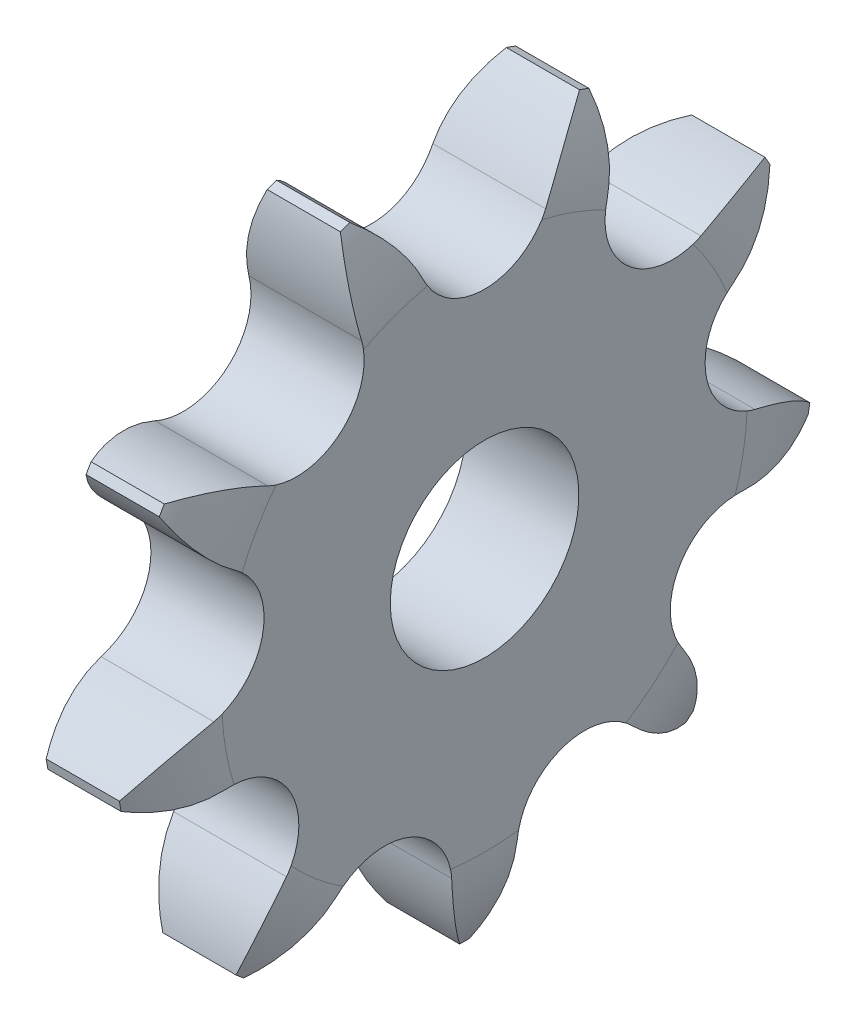
SolidWorks part; units mm, degrees
ref_plane "Plane1" through (0, 0, 0) normal (0, 0, 1) x (1, 0, 0)
ref_plane "Plane2" through (0, 0, 0) normal (0, 1, 0) x (1, 0, 0)
ref_plane "Plane3" through (0, 0, 0) normal (1, 0, 0) x (0, 0, -1)
sketch "Clipboard" plane through (0, 0, 0) normal (0, 1, 0) x (1, 0, 0)
  line L0 (0, 0) -> (12.5436, -1.9867)
  line L1 (-15, 0) -> (100, 0) construction
  line L2 (0, 0) -> (-0.8416, 0.9512)
  line L3 (0, 0) -> (-11.863, 4.5341)
  line L4 (0, 0) -> (3.0618, 0.4849)
  line L5 (0, 0) -> (-2.8109, -1.0484)
  line L6 (0, 0) -> (-5.9685, -4.027)
  line L7 (-0.8416, 0.9512) -> (8.4161, 2.5835)
  line L8 (-76.2, 38.1) -> (-75.2, 38.1)
  line L9 (-73.4259, 41.6592) -> (-72.8306, 41.7344)
  line L10 (-73.4741, 12.7512) -> (-59.5541, 12.7512)
  circle A0 centre (0, 0) radius 4.255
  circle A1 centre (0, 0) radius 10.9305
  circle A2 centre (0, 0) radius 25
  dimension "Dr" = 8.51
  dimension "MHD" = 21.861
  dimension "Hub_dia" = 50
  dimension "Num_teeth" = 9
  dimension "Pitch" = 12.7
  dimension "Width" = 3.1
  dimension "Side_relief" = 1.27
  dimension "Side_radius" = 12.7
  dimension "Overall_len" = 3
  dimension "Show_teeth" = 9
  dimension "Thickness" = 7.2
  dimension "OAL" = 9.4005
  dimension "T_dim" = 1
  dimension "Fillet_rad" = 0.6
  dimension "Face_width" = 7.2
  dimension "Num_strands" = 1
  dimension "Transv_pitch" = 13.92
  dimension "Plate_wid" = 11.8
sketch "BasProSke" plane through (0, 0, 0) normal (0, 1, 0) x (1, 0, 0)
  line L0 (-10, 0) -> (60, 0) construction
  line L1 (0, 0) -> (0, 16.7129)
  line L2 (0, 0) -> (7.2, 0)
  line L3 (7.2, 0) -> (7.2, 16.7129)
  line L4 (5.93, 22.2487) -> (1.27, 22.2487)
  arc A0 (0, 16.7129) -> (1.27, 22.2487) centre (12.7, 16.7129) cw
  arc A1 (7.2, 16.7129) -> (5.93, 22.2487) centre (-5.5, 16.7129) ccw
  dimension "Thickness" = 7.2
  dimension "D1" = 12.7
  dimension "G1" = 1.27
  dimension "G2" = 1.27
  dimension "Diameter" = 44.4973
revolve "Base-Revolve" add sketch "BasProSke" angle 360 about L0
sketch "TooCutSke" plane through (0, 0, 0) normal (1, 0, 0) x (0, 0, -1)
  line L0 (0, 18.6087) -> (3.8949, 16.7925) construction
  line L1 (0, 0) -> (0, 107) construction
  line L2 (0, 18.6087) -> (-10, 18.6087) construction
  line L3 (0, 18.6087) -> (-3.8949, 16.7925) construction
  arc A0 (3.8949, 16.7925) -> (7.8075, 21.3669) centre (14.0756, 12.0451) cw
  arc A1 (3.8949, 16.7925) -> (-3.8949, 16.7925) centre (0, 18.6087) cw
  arc A2 (-3.8949, 16.7925) -> (-7.8075, 21.3669) centre (-14.0756, 12.0451) ccw
  arc A3 (7.8075, 21.3669) -> (-7.8075, 21.3669) centre (0, 0) ccw
  dimension "R1" = 4.2976
  dimension "R2" = 11.2332
  dimension "Overcut" = 22.7487
  dimension "Seat_radius" = 18.6087
  dimension "X" = 130
extrude "ToothCut" cut sketch "TooCutSke" along normal through all
pattern_circular "TeethCuts" count 9 every 40 about axis through (-10, 0, 0) along (1, 0, 0) of "ToothCut"
sketch "HubNeaOneSke" plane through (0, 0, 0) normal (-1, 0, 0) x (0, 0, 1)
  circle A0 centre (0, 0) radius 10.9305
  dimension "Diameter" = 21.861
extrude "HubNearOne" [suppressed] add sketch "HubNeaOneSke" along normal blind 2.2005
fillet "HubNearOneFillet" [suppressed] radius 0.6
sketch "HubNeaBotSke" plane through (0, 0, 0) normal (-1, 0, 0) x (0, 0, 1)
  circle A0 centre (0, 0) radius 10.9305
  dimension "Diameter" = 21.861
extrude "HubNearBoth" [suppressed] add sketch "HubNeaBotSke" along normal blind 1.1003
fillet "HubNearBothFillet" [suppressed] radius 0.6
ref_plane "FarPln" through (7.2, 0, 0) normal (1, 0, 0) x (0, 0, -1)
sketch "HubFarSke" plane through (7.2, 0, 0) normal (1, 0, 0) x (0, 0, -1)
  circle A0 centre (0, 0) radius 10.9305
  dimension "Diameter" = 21.861
extrude "HubFar" [suppressed] add sketch "HubFarSke" along normal blind 1.1003
fillet "HubFarFillet" [suppressed] radius 0.6
sketch "BorSke" plane through (0, 0, 0) normal (1, 0, 0) x (0, 0, -1)
  circle A0 centre (0, 0) radius 6
  dimension "Diameter" = 12
extrude "Bore" cut sketch "BorSke" along normal mid plane 18.801
sketch "KeySke" plane through (0, 0, 0) normal (1, 0, 0) x (0, 0, -1)
  line L0 (-1, 0) -> (-1, 7)
  line L1 (-1, 7) -> (1, 7)
  line L2 (1, 7) -> (1, 0)
  line L3 (0, 0) -> (0, 34) construction
  line L4 (-1, 0) -> (1, 0)
  dimension "Offset" = 7
  dimension "Width" = 2
extrude "Keyway" [suppressed] cut sketch "KeySke" along normal mid plane 18.801
pattern_circular "Keyway2" [suppressed] count 2 every 90 about axis through (-10, 0, 0) along (1, 0, 0)
equation "' \"Pitch@Clipboard\" = 12.7"
equation "' \"Num_strands@Clipboard\" = 1"
equation "' \"Num_teeth@Clipboard\" = 9"
equation "' \"Hub_dia@Clipboard\" = 50"
equation "' \"Overall_len@Clipboard\" = 3"
equation "' \"Diameter@BorSke\" = 12"
equation "' \"T_dim@Clipboard\" = 1"
equation "' \"Width@KeySke\" = 2"
equation "' \"Dr@Clipboard\" = 8.51"
equation "' \"Face_width@Clipboard\" = 7.2"
equation "' \"Side_radius@Clipboard\" = 12.7"
equation "' \"Side_relief@Clipboard\" = 1.27"
equation "' \"Transv_pitch@Clipboard\" = 13.92"
equation "' \"Show_teeth@Clipboard\" = 9"
equation "' \"Fillet_rad@Clipboard\" = 0.6"
equation "' \"Plate_wid@Clipboard\" = 11.8"
equation "\"Num_teeth@Clipboard\" = int( \"Num_teeth@Clipboard\" )"
equation "\"Num_teeth@Clipboard\" = ((sgn( \"Num_teeth@Clipboard\" - 5.0)+1)*( \"Num_teeth@Clipboard\" - 5.0))/2 +5.0"
equation "\"Num_teeth@Clipboard\" = ((sgn( \"Num_teeth@Clipboard\" - 200.0)-1)*( \"Num_teeth@Clipboard\" - 200.0))/-2 +200.0"
equation "\"MHD@Clipboard\" = \"Pitch@Clipboard\" * (1.0 / tan(3.14159265 / \"Num_teeth@Clipboard\" )) - 1.04 * \"Plate_wid@Clipboard\" - 0.76"
equation "\"Thickness@Clipboard\"  = \"Face_width@Clipboard\" + (\"Num_strands@Clipboard\" - 1) * \"Transv_pitch@Clipboard\""
equation "\"OAL@Clipboard\" = \"Thickness@Clipboard\" + 2 * \"Fillet_rad@Clipboard\" + 1"
equation "\"MHD@Clipboard\" = ((sgn( \"MHD@Clipboard\" - \"Hub_dia@Clipboard\" )-1)*( \"MHD@Clipboard\" - \"Hub_dia@Clipboard\" ))/-2+ \"Hub_dia@Clipboard\""
equation "\"OAL@Clipboard\" = ((sgn( \"OAL@Clipboard\" - \"Overall_len@Clipboard\" )+1)*( \"OAL@Clipboard\" - \"Overall_len@Clipboard\" ))/2 + \"Overall_len@Clipboard\" + 0.0005"
equation "\"Num_teeth@TeethCuts\" = int( \"Show_teeth@Clipboard\" ) + 1"
equation "\"Num_teeth@TeethCuts\" = ((sgn( \"Num_teeth@TeethCuts\" - \"Num_teeth@Clipboard\" )-1)*( \"Num_teeth@TeethCuts\" - \"Num_teeth@Clipboard\" ))/-2+ \"Num_teeth@Clipboard\""
equation "\"Num_teeth@TeethCuts\" = ((sgn( \"Num_teeth@TeethCuts\" - 2.0)+1)*( \"Num_teeth@TeethCuts\" - 2.0))/2 +2.0"
equation "\"Angle@TeethCuts\" = 360.0 / \"Num_teeth@Clipboard\""
equation "\"Seat_radius@TooCutSke\" = ( \"Pitch@Clipboard\" / 2.0) / sin(3.14159265 / \"Num_teeth@Clipboard\" ) - \"Dr@Clipboard\" / 2.0 + \"Dr@Clipboard\" * 0.505"
equation "\"R1@TooCutSke\"  = \"Dr@Clipboard\" * 0.505"
equation "\"X@TooCutSke\" = 140.0 - (90.0 / \"Num_teeth@Clipboard\")"
equation "\"R2@TooCutSke\" = 0.12 * \"Dr@Clipboard\" * ( \"Num_teeth@Clipboard\" + 2.0)"
equation "\"Overcut@TooCutSke\" = 0.5 + 0.625 * \"Pitch@Clipboard\" - 0.5 * \"Dr@Clipboard\"  +  \"Pitch@Clipboard\" / 2.0 / sin(3.14159265 / \"Num_teeth@Clipboard\" )"
equation "\"Diameter@BasProSke\" = 2.0 * ( 0.625 * \"Pitch@Clipboard\" - 0.5 * \"Dr@Clipboard\"  +  \"Pitch@Clipboard\" / 2.0 / sin(3.14159265 / \"Num_teeth@Clipboard\" ))"
equation "\"Thickness@BasProSke\"  = \"Thickness@Clipboard\""
equation "\"G1@BasProSke\" =  \"Side_relief@Clipboard\""
equation "\"G2@BasProSke\" =  \"Side_relief@Clipboard\""
equation "\"D1@BasProSke\" =  \"Side_radius@Clipboard\""
equation "\"Diameter@HubNeaOneSke\" = \"MHD@Clipboard\""
equation "\"Length@HubNearOne\" = \"OAL@Clipboard\" - \"Thickness@BasProSke\""
equation "\"Diameter@HubNeaBotSke\" = \"MHD@Clipboard\""
equation "\"Length@HubNearBoth\" = ( \"OAL@Clipboard\" - \"Thickness@BasProSke\" ) / 2.0"
equation "\"D1@HubNearOneFillet\" = \"Fillet_rad@Clipboard\""
equation "\"D1@HubNearBothFillet\" = \"Fillet_rad@Clipboard\""
equation "\"Thickness@FarPln\" = \"Thickness@BasProSke\""
equation "\"Diameter@HubFarSke\" = \"MHD@Clipboard\""
equation "\"Length@HubFar\" = ( \"OAL@Clipboard\" - \"Thickness@BasProSke\" ) / 2.0"
equation "\"D1@HubFarFillet\" = \"Fillet_rad@Clipboard\""
equation "\"D1@Bore\" = \"OAL@Clipboard\" * 2.0"
equation "\"D1@Keyway\" = \"OAL@Clipboard\" * 2.0"
equation "\"Offset@KeySke\" = \"T_dim@Clipboard\" + \"Diameter@BorSke\" / 2.0"
